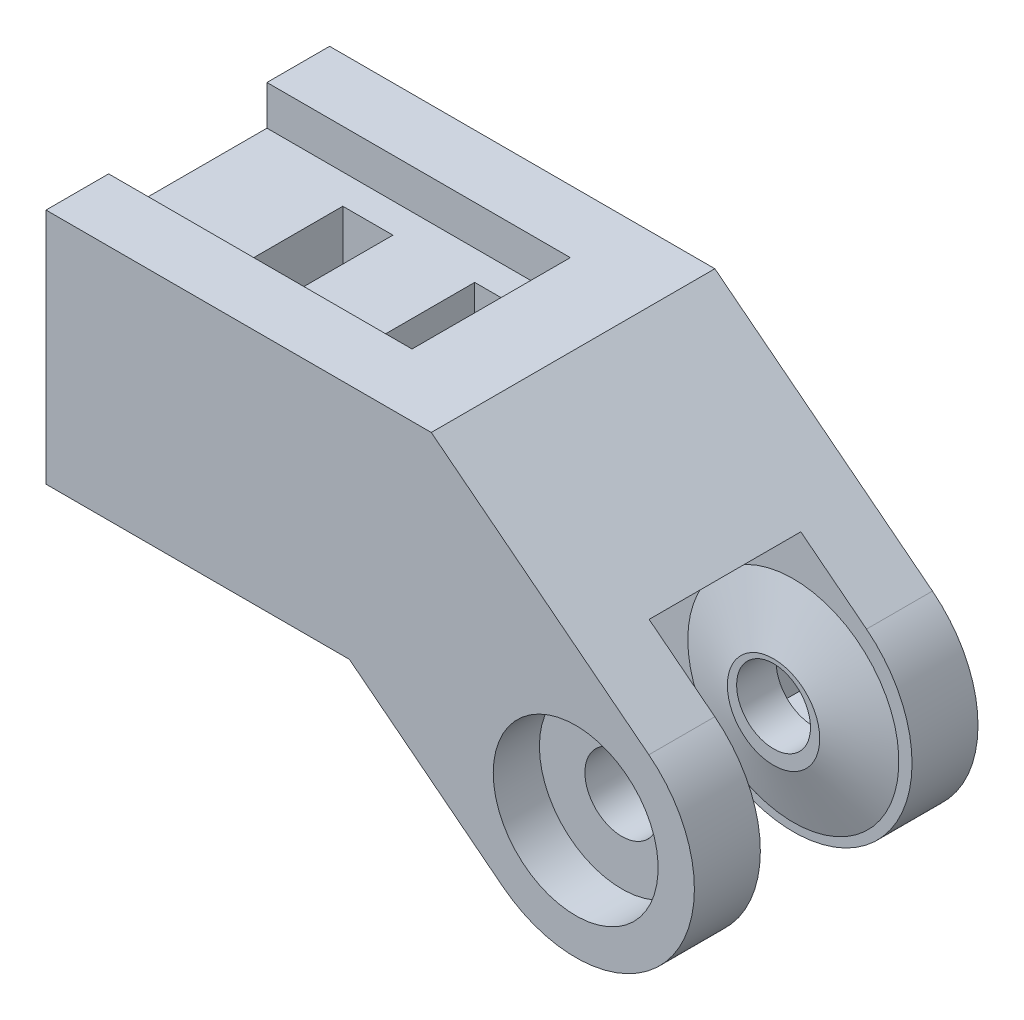
SolidWorks part; units mm, degrees
ref_plane "Front Plane" through (0, 0, 0) normal (0, 0, 1) x (1, 0, 0)
ref_plane "Top Plane" through (0, 0, 0) normal (0, 1, 0) x (1, 0, 0)
ref_plane "Right Plane" through (0, 0, 0) normal (1, 0, 0) x (0, 0, -1)
sketch "Sketch1" plane through (0, 0, 0) normal (0, 0, 1) x (1, 0, 0)
  line L0 (-40.1551, -0.8363) -> (-17.1551, -0.8363)
  line L1 (-17.1551, -0.8363) -> (-5.5478, -9.923)
  line L2 (-40.1551, -0.8363) -> (-40.1551, 17.1637)
  line L3 (-40.1551, 17.1637) -> (-10.9475, 17.1637)
  line L4 (-10.9475, 17.1637) -> (5.5478, 4.2505)
  line L5 (-5.5478, -9.923) -> (5.5478, 4.2505) construction
  arc A1 (-5.5478, -9.923) -> (5.5478, 4.2505) centre (0, -2.8363) ccw
  point P3 (0, 0)
  dimension "D3" = 23
  dimension "D1" = 18
  dimension "D2" = 18
  dimension "D4" = 20
extrude "Boss-Extrude1" add sketch "Sketch1" along normal blind 5
sketch "Sketch8" plane through (0, 0, 5) normal (0, 0, 1) x (1, 0, 0)
  circle A1 centre (0, -3.2165) radius 3.5
  dimension "D1" = 7
extrude "Boss-Extrude5" add sketch "Sketch8" along normal blind 1.5
sketch "Sketch10" plane through (0, 0, 5) normal (0, 0, 1) x (1, 0, 0)
  circle A0 centre (0, -3.2165) radius 8
loft "Loft4" add profiles "Sketch10" section "Sketch10" section face at (3.5, -3.2165, 6.5)
sketch "Sketch14" plane through (0, 0, 5) normal (0, 0, 1) x (1, 0, 0)
  line L0 (-40.1551, -0.8363) -> (-40.1551, 17.1637)
  line L1 (-40.1551, 17.1637) -> (-10.9475, 17.1637)
  line L2 (-10.5279, -6.0244) -> (-17.1551, -0.8363)
  line L3 (-10.9475, 17.1637) -> (-40.1551, 17.1637) construction
  line L4 (5.5478, 4.2505) -> (-10.9475, 17.1637) construction
  line L7 (-17.1551, -0.8363) -> (-40.1551, -0.8363)
  line L8 (-10.9475, 17.1637) -> (0.5678, 8.1491)
  arc A0 (0.5678, 8.1491) -> (-10.5279, -6.0244) centre (0, -2.8363) ccw
  arc A1 (-5.5478, -9.923) -> (5.5478, 4.2505) centre (0, -2.8363) ccw construction
  dimension "D1" = 11
extrude "Boss-Extrude7" add sketch "Sketch14" along normal blind 5.75 contours A0 L2 L7 L0 L1 L8
sketch "Sketch15" plane through (0, 0, 0) normal (0, 0, -1) x (-1, 0, 0)
  circle A0 centre (0, -2.8363) radius 2.8
  arc A1 (-5.5478, 4.2505) -> (5.5478, -9.923) centre (0, -2.8363) ccw construction
  dimension "D1" = 5.6
extrude "Cut-Extrude7" cut sketch "Sketch15" against normal blind 10
mirror "Mirror1" about plane through (0, -2.8363, 10.75) normal (0, 0, 1) of bodies 117 114
sketch "Sketch6" plane through (0, 0, 5) normal (0, 0, 1) x (1, 0, 0)
  line L1 (4.2, 1.3637) -> (-4.2, 1.3637)
  line L2 (4.2, 1.3637) -> (4.2, -7.0363)
  line L3 (4.2, -7.0363) -> (-4.2, -7.0363)
  line L4 (-4.2, 1.3637) -> (-4.2, -7.0363)
  line L5 (4.2, 1.3637) -> (-4.2, -7.0363) construction
  line L6 (4.2, -7.0363) -> (-4.2, 1.3637) construction
  point P0 (0, -2.8363)
  dimension "D1" = 8.4
extrude "nut-cut" cut sketch "Sketch6" against normal through all from offset 1.5 offset against normal yes
sketch "Sketch16" plane through (-40.1551, 0, 0) normal (-1, 0, 0) x (0, 0, 1)
  line L0 (21.5, -0.8363) -> (0, -0.8363) construction
  line L1 (4.75, -0.8363) -> (16.75, -0.8363)
  line L2 (4.75, -0.8363) -> (4.75, 2.1637)
  line L3 (4.75, 2.1637) -> (16.75, 2.1637)
  line L4 (16.75, -0.8363) -> (16.75, 2.1637)
  line L6 (21.5, 17.1637) -> (0, 17.1637) construction
  line L8 (16.75, 17.1637) -> (4.75, 17.1637)
  line L9 (16.75, 17.1637) -> (16.75, 14.1637)
  line L11 (16.75, 14.1637) -> (4.75, 14.1637)
  line L12 (4.75, 17.1637) -> (4.75, 14.1637)
  point P7 (10.75, 17.1637)
  dimension "D1" = 12
  dimension "D2" = 3
extrude "Cut-Extrude8" cut sketch "Sketch16" against normal blind 23
sketch "Sketch17" plane through (-40.1551, 0, 0) normal (-1, 0, 0) x (0, 0, 1)
  line L0 (21.5, -0.8363) -> (16.75, -0.8363) construction
  line L1 (21.5, 17.1637) -> (21.5, -0.8363) construction
  circle A0 centre (10.75, 8.1637) radius 2.35
  dimension "D1" = 4.7
  dimension "D2" = 9
  dimension "D3" = 10.75
extrude "Cut-Extrude9" cut sketch "Sketch17" against normal blind 28
sketch "Sketch19" plane through (0, 0, 16.5) normal (0, 0, 1) x (1, 0, 0)
  circle A0 centre (0, -2.8363) radius 6.25
  dimension "D1" = 12.5
extrude "Cut-Extrude10" cut sketch "Sketch19" along normal through all from offset 1.5
sketch "Sketch20" plane through (-40.1551, 0, 0) normal (-1, 0, 0) x (0, 0, 1)
  line L0 (7, 14.1637) -> (14.5, 14.1637)
  line L1 (10.75, 3.8336) -> (14.5, 5.9987)
  line L2 (14.5, 5.9987) -> (14.5, 14.1637)
  line L3 (14.5, 10.3288) -> (10.75, 12.4939) construction
  line L4 (10.75, 12.4939) -> (7, 10.3288) construction
  line L5 (7, 14.1637) -> (7, 5.9987)
  line L6 (7, 5.9987) -> (10.75, 3.8336)
  line L7 (4.75, 14.1637) -> (16.75, 14.1637) construction
  line L8 (4.75, 14.1637) -> (16.75, 14.1637) construction
  line L9 (7, 14.1637) -> (14.5, 14.1637)
  line L10 (14.5, 14.1637) -> (14.4669, 14.1279)
  circle A0 centre (10.75, 8.1637) radius 3.75 construction
  dimension "D1" = 7.5
extrude "Cut-Extrude11" cut sketch "Sketch20" against normal blind 3.8 from offset 8 offset against normal yes
pattern_linear "LPattern1" count 2 spacing 10 along (1, 0, 0) of "Cut-Extrude11"
sketch "Sketch22" plane through (0, 0, 6.5) normal (0, 0, -1) x (-1, 0, 0)
  circle A0 centre (0, -2.8363) radius 3.0518
extrude "Boss-Extrude8" [suppressed] add sketch "Sketch22" along normal blind 0.65
sketch "Sketch23" plane through (0, 0, 18) normal (0, 0, 1) x (1, 0, 0)
  circle A0 centre (0, -2.8363) radius 3.919
extrude "Boss-Extrude9" [suppressed] add sketch "Sketch23" against normal blind 0.65
